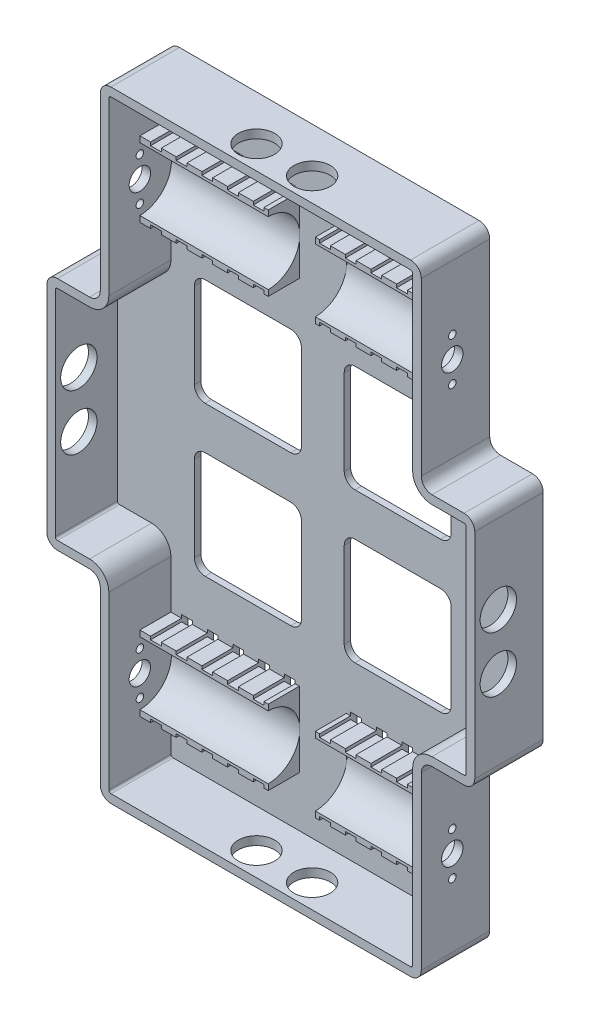
SolidWorks part; units mm, degrees
ref_plane "Front Plane" through (0, 0, 0) normal (0, 0, 1) x (1, 0, 0)
ref_plane "Top Plane" through (0, 0, 0) normal (0, 1, 0) x (1, 0, 0)
ref_plane "Right Plane" through (0, 0, 0) normal (1, 0, 0) x (0, 0, -1)
sketch "Sketch1" plane through (0, 0, 0) normal (0, 0, 1) x (1, 0, 0)
  line L0 (-75, -145) -> (75, -145)
  line L1 (75, -145) -> (75, -55)
  line L2 (75, -55) -> (100, -55)
  line L3 (100, -55) -> (100, 55)
  line L4 (100, 55) -> (75, 55)
  line L5 (75, 55) -> (75, 145)
  line L6 (75, 145) -> (-75, 145)
  line L7 (-75, 145) -> (-75, 55)
  line L8 (-75, 55) -> (-100, 55)
  line L9 (-100, 55) -> (-100, -55)
  line L10 (-100, -55) -> (-75, -55)
  line L11 (-75, -55) -> (-75, -145)
  line L12 (-75, 55) -> (75, 55) construction
  line L13 (75, 55) -> (75, -55) construction
  line L14 (75, -55) -> (-75, -55) construction
  line L15 (-75, -55) -> (-75, 55) construction
  line L16 (0, 55) -> (0, -55) construction
  dimension "D1" = 200
  dimension "D2" = 290
  dimension "D3" = 90
  dimension "D4" = 150
extrude "Boss-Extrude1" add sketch "Sketch1" along normal blind 3
fillet "Fillet1" radius 5 12 edges at (-75, -55, 1.5) (-100, -55, 1.5) (-75, 145, 1.5) (75, 145, 1.5) (75, 55, 1.5) (100, 55, 1.5) (100, -55, 1.5) (75, -55, 1.5) (75, -145, 1.5) (-75, -145, 1.5) (-75, 55, 1.5) (-100, 55, 1.5)
sketch "Sketch2" plane through (0, 0, 3) normal (0, 0, 1) x (1, 0, 0)
  line L0 (-96, 50) -> (-96, -50)
  line L1 (-95, -51) -> (-80, -51)
  line L2 (-71, -60) -> (-71, -140)
  line L3 (-70, -141) -> (70, -141)
  line L4 (71, -140) -> (71, -60)
  line L5 (80, -51) -> (95, -51)
  line L6 (96, -50) -> (96, 50)
  line L7 (95, 51) -> (80, 51)
  line L8 (71, 60) -> (71, 140)
  line L9 (70, 141) -> (-70, 141)
  line L10 (-71, 140) -> (-71, 60)
  line L11 (-80, 51) -> (-95, 51)
  line L12 (-100, 50) -> (-100, -50)
  line L13 (-95, -55) -> (-80, -55)
  line L14 (-75, -60) -> (-75, -140)
  line L15 (-70, -145) -> (70, -145)
  line L16 (75, -140) -> (75, -60)
  line L17 (80, -55) -> (95, -55)
  line L18 (100, -50) -> (100, 50)
  line L19 (95, 55) -> (80, 55)
  line L20 (75, 60) -> (75, 140)
  line L21 (70, 145) -> (-70, 145)
  line L22 (-75, 140) -> (-75, 60)
  line L23 (-80, 55) -> (-95, 55)
  line L24 (-100, 50) -> (-100, -50)
  line L25 (-95, -55) -> (-80, -55)
  line L26 (-75, -60) -> (-75, -140)
  line L27 (-70, -145) -> (70, -145)
  line L28 (75, -140) -> (75, -60)
  line L29 (80, -55) -> (95, -55)
  line L30 (100, -50) -> (100, 50)
  line L31 (95, 55) -> (80, 55)
  line L32 (75, 60) -> (75, 140)
  line L33 (70, 145) -> (-70, 145)
  line L34 (-75, 140) -> (-75, 60)
  line L35 (-80, 55) -> (-95, 55)
  arc A0 (-96, -50) -> (-95, -51) centre (-95, -50) ccw
  arc A1 (-71, -60) -> (-80, -51) centre (-80, -60) ccw
  arc A2 (-71, -140) -> (-70, -141) centre (-70, -140) ccw
  arc A3 (70, -141) -> (71, -140) centre (70, -140) ccw
  arc A4 (80, -51) -> (71, -60) centre (80, -60) ccw
  arc A5 (95, -51) -> (96, -50) centre (95, -50) ccw
  arc A6 (96, 50) -> (95, 51) centre (95, 50) ccw
  arc A7 (71, 60) -> (80, 51) centre (80, 60) ccw
  arc A8 (71, 140) -> (70, 141) centre (70, 140) ccw
  arc A9 (-70, 141) -> (-71, 140) centre (-70, 140) ccw
  arc A10 (-80, 51) -> (-71, 60) centre (-80, 60) ccw
  arc A11 (-95, 51) -> (-96, 50) centre (-95, 50) ccw
  arc A12 (-100, -50) -> (-95, -55) centre (-95, -50) ccw
  arc A13 (-75, -60) -> (-80, -55) centre (-80, -60) ccw
  arc A14 (-75, -140) -> (-70, -145) centre (-70, -140) ccw
  arc A15 (70, -145) -> (75, -140) centre (70, -140) ccw
  arc A16 (80, -55) -> (75, -60) centre (80, -60) ccw
  arc A17 (95, -55) -> (100, -50) centre (95, -50) ccw
  arc A18 (100, 50) -> (95, 55) centre (95, 50) ccw
  arc A19 (75, 60) -> (80, 55) centre (80, 60) ccw
  arc A20 (75, 140) -> (70, 145) centre (70, 140) ccw
  arc A21 (-70, 145) -> (-75, 140) centre (-70, 140) ccw
  arc A22 (-80, 55) -> (-75, 60) centre (-80, 60) ccw
  arc A23 (-95, 55) -> (-100, 50) centre (-95, 50) ccw
  arc A24 (-100, -50) -> (-95, -55) centre (-95, -50) ccw
  arc A25 (-75, -60) -> (-80, -55) centre (-80, -60) ccw
  arc A26 (-75, -140) -> (-70, -145) centre (-70, -140) ccw
  arc A27 (70, -145) -> (75, -140) centre (70, -140) ccw
  arc A28 (80, -55) -> (75, -60) centre (80, -60) ccw
  arc A29 (95, -55) -> (100, -50) centre (95, -50) ccw
  arc A30 (100, 50) -> (95, 55) centre (95, 50) ccw
  arc A31 (75, 60) -> (80, 55) centre (80, 60) ccw
  arc A32 (75, 140) -> (70, 145) centre (70, 140) ccw
  arc A33 (-70, 145) -> (-75, 140) centre (-70, 140) ccw
  arc A34 (-80, 55) -> (-75, 60) centre (-80, 60) ccw
  arc A35 (-95, 55) -> (-100, 50) centre (-95, 50) ccw
  dimension "D1" = 0
  dimension "D2" = 4
extrude "Boss-Extrude2" add sketch "Sketch2" along normal blind 29
sketch "Sketch3" plane through (-75, 0, 0) normal (-1, 0, 0) x (0, 0, 1)
  line L0 (0, -100) -> (17.5, -100) construction
  line L1 (0, -60) -> (0, -140) construction
  line L2 (17.5, -90) -> (17.5, -110) construction
  circle A0 centre (17.5, -100) radius 5
  circle A1 centre (17.5, -90) radius 1.75
  circle A2 centre (17.5, -110) radius 1.75
  dimension "D1" = 3.5
  dimension "D3" = 10
  dimension "D2" = 20
  dimension "D4" = 17.5
extrude "Cut-Extrude1" cut sketch "Sketch3" against normal blind 29
sketch "Sketch4" plane through (0, 0, 3) normal (0, 0, 1) x (1, 0, 0)
  line L0 (-71, -60) -> (-71, -140) construction
  line L1 (-71, -82.5) -> (-11, -82.5)
  line L2 (-71, -82.5) -> (-71, -117.5)
  line L3 (-71, -117.5) -> (-11, -117.5)
  line L4 (-11, -82.5) -> (-11, -117.5)
  line L5 (-71, -100) -> (-75, -100) construction
  line L6 (-75, -60) -> (-75, -140) construction
  dimension "D1" = 35
  dimension "D2" = 60
extrude "Boss-Extrude3" add sketch "Sketch4" along normal blind 14.5
sketch "Sketch5" plane through (-11, 0, 0) normal (1, 0, 0) x (0, 0, -1)
  line L0 (-17.5, -117.5) -> (-17.5, -82.5) construction
  circle A0 centre (-17.5, -100) radius 14.75
  dimension "D1" = 29.5
extrude "Cut-Extrude2" cut sketch "Sketch5" against normal blind 60
sketch "Sketch7" plane through (0, 0, 17.5) normal (0, 0, 1) x (1, 0, 0)
  line L0 (-66, -84) -> (-66, -116) construction
  line L1 (-66, -116) -> (-61, -116)
  line L2 (-66, -116) -> (-66, -119)
  line L3 (-66, -119) -> (-61, -119)
  line L4 (-61, -116) -> (-61, -119)
  line L5 (-66, -84) -> (-61, -84)
  line L6 (-66, -84) -> (-66, -81)
  line L7 (-66, -81) -> (-61, -81)
  line L8 (-61, -84) -> (-61, -81)
  line L9 (-61, -116) -> (-61, -84) construction
  line L10 (-66, -100) -> (-71, -100) construction
  line L11 (-71, -60) -> (-71, -140) construction
  dimension "D1" = 5
  dimension "D2" = 32
  dimension "D3" = 3
  dimension "D4" = 5
extrude "Cut-Extrude3" cut sketch "Sketch7" against normal through all
sketch "Sketch8" plane through (-66, 0, 0) normal (1, 0, 0) x (0, 0, -1)
  line L0 (0, -84) -> (0, -116)
  line L1 (0, -116) -> (-3, -116)
  line L2 (-3, -116) -> (-3, -84) construction
  line L3 (0, -84) -> (-17.5, -84) construction
  line L4 (-3, -84) -> (0, -84)
  line L5 (-3, -84) -> (-1.5, -85.5)
  line L6 (-1.5, -85.5) -> (-1.5, -114.5)
  line L7 (-1.5, -114.5) -> (-3, -116)
  line L8 (-1.5, -100) -> (0, -100) construction
  dimension "D1" = 1.5
  dimension "D2" = 3
  dimension "D3" = 1.5
extrude "Cut-Extrude4" cut sketch "Sketch8" along normal blind 5
pattern_linear "LPattern1" count 5 spacing 12 along (1, 0, 0) of "Cut-Extrude3", "Cut-Extrude4"
mirror "Mirror1" about plane through (0, 0, 0) normal (1, 0, 0) of "LPattern1", "Cut-Extrude4", "Cut-Extrude3", "Cut-Extrude1", "Boss-Extrude3", "Cut-Extrude2" second plane through (0, 0, 0) second plane normal (0, 1, 0)
sketch "Sketch9" [suppressed] plane through (0, 0, 3) normal (0, 0, 1) x (1, 0, 0)
  line L0 (-60, -40) -> (-40, -40)
  line L1 (-65, 40) -> (65, 40) construction
  line L2 (-65, 40) -> (-65, -40) construction
  line L3 (-65, -40) -> (65, -40) construction
  line L4 (65, 40) -> (65, -40) construction
  line L5 (-65, 40) -> (65, -40) construction
  line L6 (-65, -40) -> (65, 40) construction
  line L7 (-35, -65) -> (35, -65) construction
  line L8 (-35, -65) -> (-35, 65) construction
  line L9 (-35, 65) -> (35, 65) construction
  line L10 (35, -65) -> (35, 65) construction
  line L11 (-35, -65) -> (35, 65) construction
  line L12 (-35, 65) -> (35, -65) construction
  line L13 (-35, -45) -> (-35, -60)
  line L14 (-30, -65) -> (30, -65)
  line L15 (35, -60) -> (35, -45)
  line L16 (40, -40) -> (60, -40)
  line L17 (65, -35) -> (65, 35)
  line L18 (60, 40) -> (40, 40)
  line L19 (35, 45) -> (35, 60)
  line L20 (30, 65) -> (-30, 65)
  line L21 (-35, 60) -> (-35, 45)
  line L22 (-40, 40) -> (-60, 40)
  line L23 (-65, 35) -> (-65, -35)
  arc A0 (-60, -40) -> (-65, -35) centre (-60, -35) cw
  arc A1 (-40, -40) -> (-35, -45) centre (-40, -45) cw
  arc A2 (-35, -60) -> (-30, -65) centre (-30, -60) ccw
  arc A3 (30, -65) -> (35, -60) centre (30, -60) ccw
  arc A4 (35, -45) -> (40, -40) centre (40, -45) cw
  arc A5 (60, -40) -> (65, -35) centre (60, -35) ccw
  arc A6 (65, 35) -> (60, 40) centre (60, 35) ccw
  arc A7 (40, 40) -> (35, 45) centre (40, 45) cw
  arc A8 (35, 60) -> (30, 65) centre (30, 60) ccw
  arc A9 (-30, 65) -> (-35, 60) centre (-30, 60) ccw
  arc A10 (-35, 45) -> (-40, 40) centre (-40, 45) cw
  arc A11 (-60, 40) -> (-65, 35) centre (-60, 35) ccw
  point P0 (0, 0)
  point P6 (0, 0)
  point P20 (-35, -40)
  point P29 (35, -40)
  point P38 (35, 40)
  point P47 (-35, 40)
  dimension "D5" = 5
  dimension "D1" = 80
  dimension "D2" = 70
  dimension "D3" = 130
  dimension "D4" = 130
sketch "Sketch11" plane through (0, 145, 0) normal (0, 1, 0) x (1, 0, 0)
  line L0 (-13, -21) -> (13, -21) construction
  line L1 (0, -21) -> (0, 0) construction
  line L2 (70, -32) -> (-70, -32) construction
  circle A0 centre (-13, -21) radius 8.5
  circle A1 centre (13, -21) radius 8.5
  dimension "D1" = 17
  dimension "D2" = 26
  dimension "D3" = 11
extrude "Cut-Extrude6" cut sketch "Sketch11" against normal up to next
mirror "Mirror2" about plane through (0, 0, 0) normal (0, 1, 0) of "Cut-Extrude6"
sketch "Sketch12" plane through (100, 0, 0) normal (1, 0, 0) x (0, 0, -1)
  line L0 (-21, 13) -> (-21, -13) construction
  line L1 (-21, 0) -> (0, 0) construction
  line L2 (-32, -50) -> (-32, 50) construction
  circle A0 centre (-21, 13) radius 8.5
  circle A1 centre (-21, -13) radius 8.5
  dimension "D1" = 17
  dimension "D2" = 26
  dimension "D3" = 11
extrude "Cut-Extrude7" cut sketch "Sketch12" against normal through all
sketch "Sketch13" plane through (0, 0, 0) normal (0, 0, -1) x (-1, 0, 0)
  line L1 (-55, 60) -> (-15, 60)
  line L2 (-60, 55) -> (-60, 15)
  line L3 (-55, 10) -> (-15, 10)
  line L4 (-10, 55) -> (-10, 15)
  line L5 (-60, 60) -> (-10, 10) construction
  line L6 (-60, 10) -> (-10, 60) construction
  arc A0 (-60, 15) -> (-55, 10) centre (-55, 15) ccw
  arc A1 (-15, 10) -> (-10, 15) centre (-15, 15) ccw
  arc A2 (-15, 60) -> (-10, 55) centre (-15, 55) cw
  arc A3 (-55, 60) -> (-60, 55) centre (-55, 55) ccw
  point P0 (-35, 35)
  dimension "D5" = 5
  dimension "D1" = 10
  dimension "D2" = 10
  dimension "D3" = 50
  dimension "D4" = 50
extrude "Cut-Extrude8" cut sketch "Sketch13" against normal through all
mirror "Mirror3" about plane through (0, 0, 0) normal (1, 0, 0) of "Cut-Extrude8" second plane through (0, 0, 0) second plane normal (0, 1, 0)
